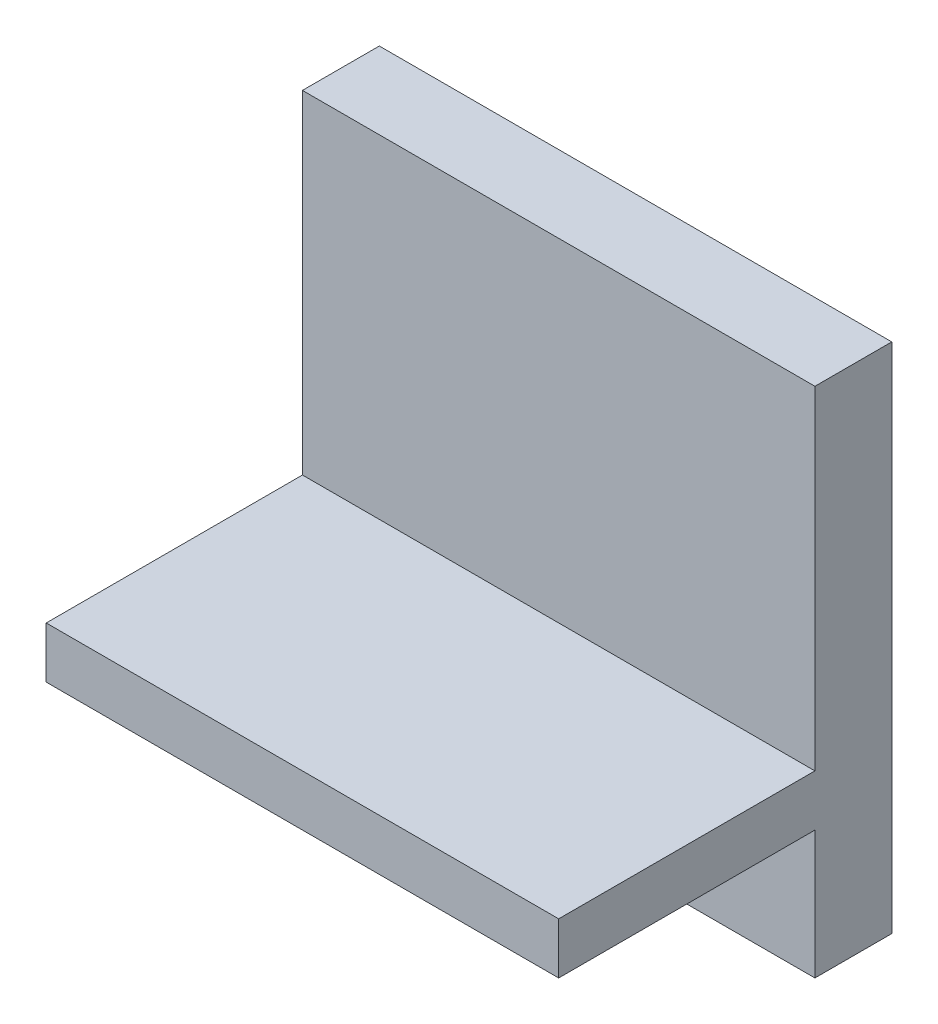
SolidWorks part; units mm, degrees
ref_plane "Alzado" through (0, 0, 0) normal (0, 0, 1) x (1, 0, 0)
ref_plane "Planta" through (0, 0, 0) normal (0, 1, 0) x (1, 0, 0)
ref_plane "Vista lateral" through (0, 0, 0) normal (1, 0, 0) x (0, 0, -1)
sketch "Croquis1" plane through (0, 0, 0) normal (0, 1, 0) x (1, 0, 0)
  line L2 (0, 0) -> (20, 0)
  line L5 (20, 0) -> (20, 3)
  line L6 (20, 3) -> (0, 3)
  line L7 (0, 3) -> (0, 0)
  dimension "D1" = 20
  dimension "D2" = 3
extrude "Saliente-Extruir7" add sketch "Croquis1" along normal blind 20
sketch "Croquis7" plane through (0, 0, 0) normal (0, 0, 1) x (1, 0, 0)
  line L0 (5, 0) -> (5, 5)
  line L1 (0, 0) -> (20, 0) construction
  line L2 (5, 5) -> (15, 5)
  line L3 (15, 5) -> (15, 0)
  line L4 (0, 20) -> (0, 0) construction
  line L6 (15, 0) -> (5, 0)
  dimension "D1" = 5
  dimension "D2" = 10
  dimension "D3" = 5
extrude "Saliente-Extruir8" add sketch "Croquis7" along normal blind 3
sketch "Croquis8" plane through (0, 0, 0) normal (0, 0, 1) x (1, 0, 0)
  line L0 (15, 5) -> (20, 5)
  line L2 (20, 20) -> (20, 0) construction
  line L3 (20, 5) -> (20, 7)
  line L4 (20, 7) -> (0, 7)
  line L5 (0, 20) -> (0, 0) construction
  line L6 (0, 7) -> (0, 5)
  line L7 (0, 5) -> (15, 5)
  dimension "D1" = 2
extrude "Saliente-Extruir10" add sketch "Croquis8" along normal blind 10
